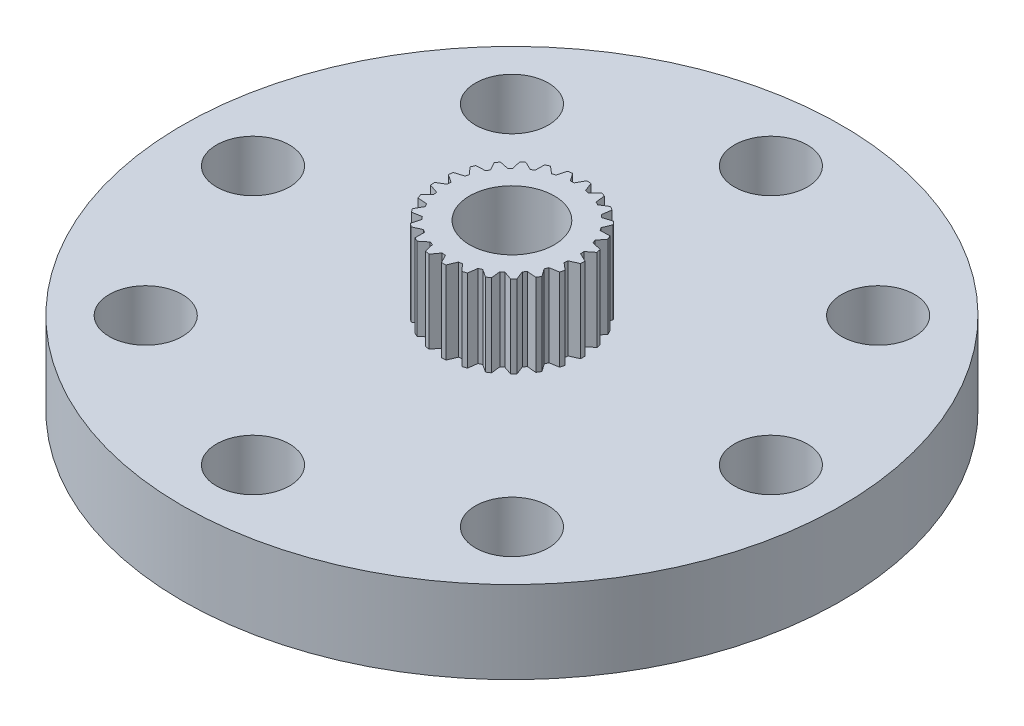
SolidWorks part; units mm, degrees
material "PLA"
ref_plane "Front Plane" through (0, 0, 0) normal (0, 0, 1) x (1, 0, 0)
ref_plane "Top Plane" through (0, 0, 0) normal (0, 1, 0) x (1, 0, 0)
ref_plane "Right Plane" through (0, 0, 0) normal (1, 0, 0) x (0, 0, -1)
sketch "Sketch1" plane through (0, 0, 0) normal (0, 1, 0) x (1, 0, 0)
  circle A0 centre (0, 0) radius 14
  dimension "D1" = 28
extrude "Boss-Extrude1" add sketch "Sketch1" along normal mid plane 3.5 contours A0
sketch "Sketch2" plane through (0, 1.75, 0) normal (0, 1, 0) x (1, 0, 0)
  line L0 (2.7822, 0.7455) -> (2.5435, 0.3349)
  line L1 (2.5435, 0.3349) -> (2.8804, 0)
  line L2 (2.8804, 0) -> (2.5435, -0.3349)
  line L3 (2.7822, -0.7455) -> (2.5435, -0.3349)
  line L4 (2.7822, -0.7455) -> (2.3701, -0.9817)
  line L5 (2.4945, -1.4402) -> (2.3701, -0.9817)
  line L6 (2.4945, -1.4402) -> (2.0353, -1.5617)
  line L7 (2.0367, -2.0367) -> (2.0353, -1.5617)
  line L8 (2.0367, -2.0367) -> (1.5617, -2.0353)
  line L9 (1.4402, -2.4945) -> (1.5617, -2.0353)
  line L10 (1.4402, -2.4945) -> (0.9817, -2.3701)
  line L11 (0.7455, -2.7822) -> (0.9817, -2.3701)
  line L12 (0.7455, -2.7822) -> (0.3349, -2.5435)
  line L13 (0, -2.8804) -> (0.3349, -2.5435)
  line L14 (0, -2.8804) -> (-0.3349, -2.5435)
  line L15 (-0.7455, -2.7822) -> (-0.3349, -2.5435)
  line L16 (-0.7455, -2.7822) -> (-0.9817, -2.3701)
  line L17 (-1.4402, -2.4945) -> (-0.9817, -2.3701)
  line L18 (-1.4402, -2.4945) -> (-1.5617, -2.0353)
  line L19 (-2.0367, -2.0367) -> (-1.5617, -2.0353)
  line L20 (-2.0367, -2.0367) -> (-2.0353, -1.5617)
  line L21 (-2.4945, -1.4402) -> (-2.0353, -1.5617)
  line L22 (-2.4945, -1.4402) -> (-2.3701, -0.9817)
  line L23 (-2.7822, -0.7455) -> (-2.3701, -0.9817)
  line L24 (-2.7822, -0.7455) -> (-2.5435, -0.3349)
  line L25 (-2.8804, 0) -> (-2.5435, -0.3349)
  line L26 (-2.8804, 0) -> (-2.5435, 0.3349)
  line L27 (-2.7822, 0.7455) -> (-2.5435, 0.3349)
  line L28 (-2.7822, 0.7455) -> (-2.3701, 0.9817)
  line L29 (-2.4945, 1.4402) -> (-2.3701, 0.9817)
  line L30 (-2.4945, 1.4402) -> (-2.0353, 1.5617)
  line L31 (-2.0367, 2.0367) -> (-2.0353, 1.5617)
  line L32 (-2.0367, 2.0367) -> (-1.5617, 2.0353)
  line L33 (-1.4402, 2.4945) -> (-1.5617, 2.0353)
  line L34 (-1.4402, 2.4945) -> (-0.9817, 2.3701)
  line L35 (-0.7455, 2.7822) -> (-0.9817, 2.3701)
  line L36 (-0.7455, 2.7822) -> (-0.3349, 2.5435)
  line L37 (0, 2.8804) -> (-0.3349, 2.5435)
  line L38 (0, 2.8804) -> (0.3349, 2.5435)
  line L39 (0.7455, 2.7822) -> (0.3349, 2.5435)
  line L40 (0.7455, 2.7822) -> (0.9817, 2.3701)
  line L41 (1.4402, 2.4945) -> (0.9817, 2.3701)
  line L42 (1.4402, 2.4945) -> (1.5617, 2.0353)
  line L43 (2.0367, 2.0367) -> (1.5617, 2.0353)
  line L44 (2.0367, 2.0367) -> (2.0353, 1.5617)
  line L45 (2.4945, 1.4402) -> (2.0353, 1.5617)
  line L46 (2.4945, 1.4402) -> (2.3701, 0.9817)
  line L47 (2.7822, 0.7455) -> (2.3701, 0.9817)
sketch "Sketch4" plane through (0, 1.75, 0) normal (0, 1, 0) x (1, 0, 0)
  circle A0 centre (0, 0) radius 5
  circle A1 centre (-7.7782, 7.7782) radius 1.025
  circle A2 centre (-7.7782, -7.7782) radius 1.025
  circle A3 centre (7.7782, -7.7782) radius 1.025
  circle A4 centre (7.7782, 7.7782) radius 1.025
  circle A5 centre (11, 0) radius 1.025
  circle A6 centre (0, -11) radius 1.025
  circle A7 centre (-11, 0) radius 1.025
  circle A8 centre (0, 11) radius 1.025
  circle A9 centre (0, 0) radius 14
hole_wizard "M2.5 Clearance Hole1" positions "Sketch5" profile "Sketch6" hole size "M2.5" standard "ANSI Metric"
sketch "Sketch5" plane through (0, 1.75, 0) normal (0, 1, 0) x (1, 0, 0)
  point P0 (-11, 0)
  point P3 (-7.7782, 7.7782)
  point P6 (0, 11)
  point P9 (7.7782, 7.7782)
  point P12 (11, 0)
  point P15 (7.7782, -7.7782)
  point P18 (0, -11)
  point P21 (-7.7782, -7.7782)
sketch "Sketch6" plane through (-11, 1.75, 0) normal (1, 0, 0) x (0, 0, 1)
  line L0 (0, 0) -> (0, 6.9313)
  line L1 (0, 6.9313) -> (1.55, 6)
  line L2 (1.55, 6) -> (1.55, 0)
  line L5 (1.55, 0) -> (0, 0)
  line L10 (0, 6.9313) -> (-1.55, 6) construction
  line L11 (0, -6.35) -> (0, 107.95) construction
  dimension "Hole Dia." = 3.1
  dimension "Hole Depth" = 6
  dimension "Drill Angle" = 118
sketch "Sketch7" plane through (0, -1.75, 0) normal (0, -1, 0) x (1, 0, 0)
  circle A0 centre (0, 0) radius 5
  dimension "D1" = 10
extrude "Cut-Extrude1" cut sketch "Sketch7" against normal blind 2.3
sketch "Sketch8" plane through (0, 1.75, 0) normal (0, 1, 0) x (1, 0, 0)
  line L0 (-0.1289, -2.6969) -> (0.0574, -3.0495)
  line L1 (-0.2813, -2.6853) -> (-0.5188, -3.0056)
  line L2 (-0.7955, -2.5802) -> (-0.7028, -2.9679)
  line L3 (-0.9403, -2.531) -> (-1.2499, -2.7821)
  line L4 (-1.4122, -2.3013) -> (-1.4188, -2.6999)
  line L5 (-1.5401, -2.2176) -> (-1.9025, -2.3839)
  line L6 (-1.9401, -1.8778) -> (-2.0457, -2.2622)
  line L7 (-2.0433, -1.765) -> (-2.4356, -1.8358)
  line L8 (-2.3461, -1.3363) -> (-2.544, -1.6824)
  line L9 (-2.418, -1.2014) -> (-2.8156, -1.1725)
  line L10 (-2.6047, -0.7108) -> (-2.8825, -0.9969)
  line L11 (-2.6408, -0.5623) -> (-3.0188, -0.4354)
  line L12 (-2.6997, -0.0407) -> (-3.0398, -0.2487)
  line L13 (-2.6977, 0.1121) -> (-3.0322, 0.329)
  line L14 (-2.625, 0.6319) -> (-3.0062, 0.5151)
  line L15 (-2.585, 0.7795) -> (-2.8551, 1.0728)
  line L16 (-2.3854, 1.2649) -> (-2.7837, 1.2465)
  line L17 (-2.31, 1.3979) -> (-2.4986, 1.7491)
  line L18 (-1.9959, 1.8184) -> (-2.3862, 1.8996)
  line L19 (-1.8898, 1.9284) -> (-1.9852, 2.3155)
  line L20 (-1.481, 2.2576) -> (-1.8388, 2.4334)
  line L21 (-1.3508, 2.3378) -> (-1.3469, 2.7365)
  line L22 (-0.873, 2.555) -> (-1.1759, 2.8142)
  line L23 (-0.727, 2.6003) -> (-0.6241, 2.9855)
  line L24 (-0.2102, 2.6918) -> (-0.4391, 3.0182)
  line L25 (-0.0575, 2.6994) -> (0.138, 3.0469)
  line L26 (0.4659, 2.6595) -> (0.3253, 3.0326)
  line L27 (0.6156, 2.6289) -> (0.8914, 2.9168)
  line L28 (1.1126, 2.4601) -> (1.0693, 2.8564)
  line L29 (1.2501, 2.3932) -> (1.5887, 2.6035)
  line L30 (1.6895, 2.1061) -> (1.746, 2.5008)
  line L31 (1.8059, 2.0071) -> (2.1863, 2.1266)
  line L32 (2.1601, 1.6198) -> (2.3131, 1.988)
  line L33 (2.2484, 1.4949) -> (2.6465, 1.5161)
  line L34 (2.4951, 1.0317) -> (2.7348, 1.3503)
  line L35 (2.5495, 0.8888) -> (2.9404, 0.8103)
  line L36 (2.6733, 0.3788) -> (2.9847, 0.6277)
  line L37 (2.6905, 0.2269) -> (3.0495, 0.0536)
  line L38 (2.6835, -0.2979) -> (3.047, -0.1342)
  line L39 (2.6623, -0.4493) -> (2.9671, -0.7065)
  line L40 (2.5251, -0.9559) -> (2.9179, -0.8878)
  line L41 (2.467, -1.0973) -> (2.6982, -1.4221)
  line L42 (2.208, -1.5539) -> (2.6055, -1.5856)
  line L43 (2.1166, -1.6764) -> (2.2597, -2.0485)
  line L44 (1.7522, -2.0542) -> (2.1293, -2.1837)
  line L45 (1.6332, -2.1501) -> (1.6793, -2.5461)
  line L46 (1.1863, -2.4254) -> (1.5193, -2.6446)
  line L47 (1.0472, -2.4887) -> (0.9934, -2.8837)
  line L48 (0.5459, -2.6442) -> (0.8139, -2.9394)
  line L49 (0.3954, -2.6709) -> (0.245, -3.0401)
  arc A0 (-0.2813, -2.6853) -> (-0.1289, -2.6969) centre (0, 0) ccw
  arc A1 (-0.7028, -2.9679) -> (-0.5188, -3.0056) centre (0, 0) ccw
  arc A2 (-0.9403, -2.531) -> (-0.7955, -2.5802) centre (0, 0) ccw
  arc A3 (-1.4188, -2.6999) -> (-1.2499, -2.7821) centre (0, 0) ccw
  arc A4 (-1.5401, -2.2176) -> (-1.4122, -2.3013) centre (0, 0) ccw
  arc A5 (-2.0457, -2.2622) -> (-1.9025, -2.3839) centre (0, 0) ccw
  arc A6 (-2.0433, -1.765) -> (-1.9401, -1.8778) centre (0, 0) ccw
  arc A7 (-2.544, -1.6824) -> (-2.4356, -1.8358) centre (0, 0) ccw
  arc A8 (-2.418, -1.2014) -> (-2.3461, -1.3363) centre (0, 0) ccw
  arc A9 (-2.8825, -0.9969) -> (-2.8156, -1.1725) centre (0, 0) ccw
  arc A10 (-2.6408, -0.5623) -> (-2.6047, -0.7108) centre (0, 0) ccw
  arc A11 (-3.0398, -0.2487) -> (-3.0188, -0.4354) centre (0, 0) ccw
  arc A12 (-2.6977, 0.1121) -> (-2.6997, -0.0407) centre (0, 0) ccw
  arc A13 (-3.0062, 0.5151) -> (-3.0322, 0.329) centre (0, 0) ccw
  arc A14 (-2.585, 0.7795) -> (-2.625, 0.6319) centre (0, 0) ccw
  arc A15 (-2.7837, 1.2465) -> (-2.8551, 1.0728) centre (0, 0) ccw
  arc A16 (-2.31, 1.3979) -> (-2.3854, 1.2649) centre (0, 0) ccw
  arc A17 (-2.3862, 1.8996) -> (-2.4986, 1.7491) centre (0, 0) ccw
  arc A18 (-1.8898, 1.9284) -> (-1.9959, 1.8184) centre (0, 0) ccw
  arc A19 (-1.8388, 2.4334) -> (-1.9852, 2.3155) centre (0, 0) ccw
  arc A20 (-1.3508, 2.3378) -> (-1.481, 2.2576) centre (0, 0) ccw
  arc A21 (-1.1759, 2.8142) -> (-1.3469, 2.7365) centre (0, 0) ccw
  arc A22 (-0.727, 2.6003) -> (-0.873, 2.555) centre (0, 0) ccw
  arc A23 (-0.4391, 3.0182) -> (-0.6241, 2.9855) centre (0, 0) ccw
  arc A24 (-0.0575, 2.6994) -> (-0.2102, 2.6918) centre (0, 0) ccw
  arc A25 (0.3253, 3.0326) -> (0.138, 3.0469) centre (0, 0) ccw
  arc A26 (0.6156, 2.6289) -> (0.4659, 2.6595) centre (0, 0) ccw
  arc A27 (1.0693, 2.8564) -> (0.8914, 2.9168) centre (0, 0) ccw
  arc A28 (1.2501, 2.3932) -> (1.1126, 2.4601) centre (0, 0) ccw
  arc A29 (1.746, 2.5008) -> (1.5887, 2.6035) centre (0, 0) ccw
  arc A30 (1.8059, 2.0071) -> (1.6895, 2.1061) centre (0, 0) ccw
  arc A31 (2.3131, 1.988) -> (2.1863, 2.1266) centre (0, 0) ccw
  arc A32 (2.2484, 1.4949) -> (2.1601, 1.6198) centre (0, 0) ccw
  arc A33 (2.7348, 1.3503) -> (2.6465, 1.5161) centre (0, 0) ccw
  arc A34 (2.5495, 0.8888) -> (2.4951, 1.0317) centre (0, 0) ccw
  arc A35 (2.9847, 0.6277) -> (2.9404, 0.8103) centre (0, 0) ccw
  arc A36 (2.6905, 0.2269) -> (2.6733, 0.3788) centre (0, 0) ccw
  arc A37 (3.047, -0.1342) -> (3.0495, 0.0536) centre (0, 0) ccw
  arc A38 (2.6623, -0.4493) -> (2.6835, -0.2979) centre (0, 0) ccw
  arc A39 (2.9179, -0.8878) -> (2.9671, -0.7065) centre (0, 0) ccw
  arc A40 (2.467, -1.0973) -> (2.5251, -0.9559) centre (0, 0) ccw
  arc A41 (2.6055, -1.5856) -> (2.6982, -1.4221) centre (0, 0) ccw
  arc A42 (2.1166, -1.6764) -> (2.208, -1.5539) centre (0, 0) ccw
  arc A43 (2.1293, -2.1837) -> (2.2597, -2.0485) centre (0, 0) ccw
  arc A44 (1.6332, -2.1501) -> (1.7522, -2.0542) centre (0, 0) ccw
  arc A45 (1.5193, -2.6446) -> (1.6793, -2.5461) centre (0, 0) ccw
  arc A46 (1.0472, -2.4887) -> (1.1863, -2.4254) centre (0, 0) ccw
  arc A47 (0.8139, -2.9394) -> (0.9934, -2.8837) centre (0, 0) ccw
  arc A48 (0.3954, -2.6709) -> (0.5459, -2.6442) centre (0, 0) ccw
  arc A49 (0.0574, -3.0495) -> (0.245, -3.0401) centre (0, 0) ccw
extrude "Boss-Extrude3" add sketch "Sketch8" along normal blind 3.5
hole_wizard "M3 Clearance Hole1" positions "Sketch9" profile "Sketch10" hole size "M3" standard "ANSI Metric"
sketch "Sketch9" plane through (0, 5.25, 0) normal (0, 1, 0) x (1, 0, 0)
  point P0 (0, 0)
sketch "Sketch10" plane through (0, 5.25, 0) normal (1, 0, 0) x (0, 0, 1)
  line L0 (0, 0) -> (0, 7.0815)
  line L1 (0, 7.0815) -> (1.8, 6)
  line L2 (1.8, 6) -> (1.8, 0)
  line L5 (1.8, 0) -> (0, 0)
  line L10 (0, 7.0815) -> (-1.8, 6) construction
  line L11 (0, -6.35) -> (0, 107.95) construction
  dimension "Hole Dia." = 3.6
  dimension "Hole Depth" = 6
  dimension "Drill Angle" = 118
